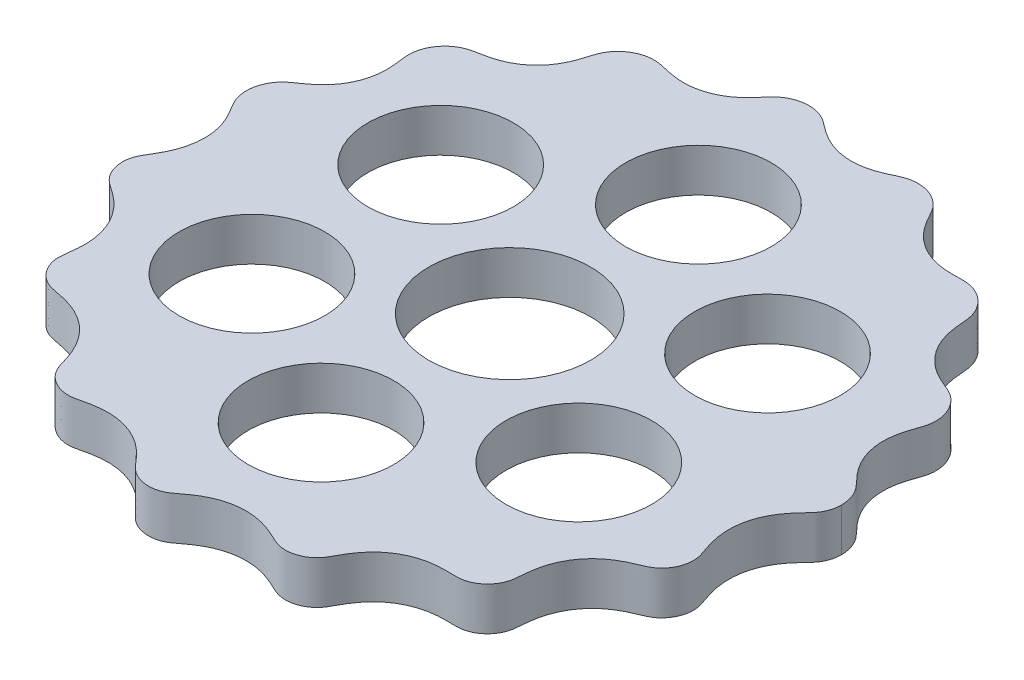
SolidWorks part; units mm, degrees
ref_plane "Front Plane" through (0, 0, 0) normal (0, 0, 1) x (1, 0, 0)
ref_plane "Top Plane" through (0, 0, 0) normal (0, 1, 0) x (1, 0, 0)
ref_plane "Right Plane" through (0, 0, 0) normal (1, 0, 0) x (0, 0, -1)
sketch "Sketch1" plane through (0, 0, 0) normal (0, 1, 0) x (1, 0, 0)
  circle A0 centre (0, 0) radius 35
  circle A1 centre (0, 35) radius 5.5
  circle A2 centre (13.3939, 32.3358) radius 5.5
  circle A3 centre (24.7487, 24.7487) radius 5.5
  circle A4 centre (32.3358, 13.3939) radius 5.5
  circle A5 centre (35, 0) radius 5.5
  circle A6 centre (32.3358, -13.3939) radius 5.5
  circle A7 centre (24.7487, -24.7487) radius 5.5
  circle A8 centre (13.3939, -32.3358) radius 5.5
  circle A9 centre (0, -35) radius 5.5
  circle A10 centre (-13.3939, -32.3358) radius 5.5
  circle A11 centre (-24.7487, -24.7487) radius 5.5
  circle A12 centre (-32.3358, -13.3939) radius 5.5
  circle A13 centre (-35, 0) radius 5.5
  circle A14 centre (-32.3358, 13.3939) radius 5.5
  circle A15 centre (-24.7487, 24.7487) radius 5.5
  circle A16 centre (-13.3939, 32.3358) radius 5.5
  point P37 (0, 0)
  dimension "D1" = 70
  dimension "D2" = 11
  dimension "D3" = 16
sketch "Sketch2" plane through (0, 0, 0) normal (0, 1, 0) x (1, 0, 0)
  line L0 (0, 0) -> (-1.25, 0)
  circle A0 centre (-1.25, 0) radius 7.5
  circle A2 centre (-1.25, 0) radius 17.5
  circle A3 centre (-1.25, 17.5) radius 6.75
  circle A4 centre (13.9054, 8.75) radius 6.75
  circle A5 centre (13.9054, -8.75) radius 6.75
  circle A6 centre (-1.25, -17.5) radius 6.75
  circle A7 centre (-16.4054, -8.75) radius 6.75
  circle A8 centre (-16.4054, 8.75) radius 6.75
  circle A9 centre (35, 0) radius 5.5 construction
  spline S0 degree 4 poles (-31.1366, 6.9847) (-31.203, 6.8351) (-31.3134, 6.5262) (-31.4099, 6.0483) (-31.4002, 5.404) (-31.2697, 4.8647) (-31.0757, 4.4461) (-30.8859, 4.1207) (-30.7324, 3.8696) (-30.5414, 3.5556) (-30.3222, 3.1725) (-30.1219, 2.7738) (-29.947, 2.3583) (-29.8196, 1.9985) (-29.7291, 1.6992) (-29.6529, 1.3958) (-29.5916, 1.0892) (-29.551, 0.8187) (-29.5259, 0.5847) (-29.5113, 0.3932) (-29.5036, 0.2322) (-29.4998, 0.0635) (-29.4996, -0.048) (-29.5028, -0.2) (-29.5088, -0.3457) (-29.52, -0.516) (-29.5395, -0.7199) (-29.5727, -0.9729) (-29.6257, -1.2689) (-29.6959, -1.5759) (-29.7851, -1.8912) (-29.9157, -2.2793) (-30.102, -2.7349) (-30.335, -3.2008) (-30.6126, -3.6776) (-30.9341, -4.194) (-31.2372, -4.7273) (-31.4061, -5.3785) (-31.4057, -6.1172) (-31.2483, -6.8003) (-30.9464, -7.4095) (-30.5187, -7.9124) (-30.0245, -8.2774) (-29.5502, -8.595) (-29.0554, -8.9568) (-28.5566, -9.3788) (-28.0713, -9.8763) (-27.6188, -10.4563) (-27.2335, -11.0884) (-26.9232, -11.7651) (-26.6937, -12.4782) (-26.5492, -13.2173) (-26.4929, -13.9285) (-26.5065, -14.6008) (-26.5673, -15.2309) (-26.6512, -15.8162) (-26.7167, -16.4473) (-26.6264, -17.121) (-26.3588, -17.7823) (-25.9182, -18.3869) (-25.3813, -18.8362) (-24.7951, -19.1235) (-24.2042, -19.2597) (-23.6514, -19.3544) (-23.1491, -19.4609) (-22.7015, -19.5807) (-22.2213, -19.7396) (-21.7138, -19.9467) (-21.1456, -20.242) (-20.5337, -20.6545) (-19.9693, -21.14) (-19.4622, -21.6938) (-19.0208, -22.3087) (-18.6716, -22.937) (-18.4029, -23.561) (-18.1966, -24.1685) (-18.0312, -24.7466) (-17.8368, -25.3596) (-17.4818, -25.9474) (-16.963, -26.4532) (-16.3026, -26.8344) (-15.6052, -27.0309) (-14.9186, -27.0444) (-14.2906, -26.9063) (-13.7073, -26.7605) (-13.0779, -26.6354) (-12.4032, -26.5561) (-11.6845, -26.5443) (-10.9313, -26.6191) (-10.1981, -26.7814) (-9.4956, -27.0274) (-8.9144, -27.311) (-8.4468, -27.5971) (-8.0759, -27.8635) (-7.7913, -28.0922) (-7.4816, -28.3679) (-7.1541, -28.6957) (-6.8107, -29.0774) (-6.4523, -29.5087) (-6.0389, -29.9524) (-5.497, -30.3164) (-4.8394, -30.5567) (-4.0956, -30.636) (-3.389, -30.5371) (-2.7605, -30.2784) (-2.2467, -29.9061) (-1.7817, -29.5409) (-1.2664, -29.1732) (-0.691, -28.8252) (-0.0469, -28.5184) (0.6654, -28.274) (1.3977, -28.1162) (2.139, -28.0466) (2.879, -28.0642) (3.6075, -28.1661) (4.2811, -28.3376) (4.8959, -28.5586) (5.4566, -28.8062) (5.9687, -29.0581) (6.5321, -29.3036) (7.1813, -29.4226) (7.8826, -29.3781) (8.5943, -29.1523) (9.1983, -28.7803) (9.6679, -28.2978) (9.9878, -27.7564) (10.2605, -27.2379) (10.5768, -26.6962) (10.9537, -26.1469) (11.4088, -25.606) (11.9502, -25.0925) (12.5482, -24.6454) (13.1945, -24.2723) (13.8806, -23.9779) (14.596, -23.7658) (15.292, -23.6421) (15.9562, -23.5904) (16.5834, -23.5873) (17.1688, -23.6104) (17.7977, -23.6041) (18.4504, -23.4386) (19.0745, -23.1016) (19.6258, -22.5981) (20.0151, -22.013) (20.2366, -21.3913) (20.3057, -20.7807) (20.3436, -20.2113) (20.4095, -19.6018) (20.5256, -18.9589) (20.7138, -18.2898) (20.9898, -17.608) (21.3446, -16.9582) (21.7755, -16.3511) (22.2783, -15.7958) (22.8461, -15.3011) (23.4339, -14.8967) (24.0229, -14.5724) (24.599, -14.31) (25.1478, -14.0899) (25.7271, -13.8311) (26.2654, -13.4161) (26.7043, -12.8537) (27.0076, -12.1698) (27.1282, -11.4802) (27.084, -10.8288) (26.9064, -10.2491) (26.7122, -9.7229) (26.5247, -9.1481) (26.3661, -8.5215) (26.2605, -7.84) (26.2278, -7.1092) (26.2792, -6.3728) (26.4175, -5.6414) (26.6435, -4.9254) (26.9163, -4.3218) (27.1985, -3.8299) (27.4942, -3.3917) (27.7933, -3.0033) (28.1536, -2.592) (28.5722, -2.1595) (28.9092, -1.79) (29.1246, -1.4556) (29.2527, -1.1931) (29.3238, -1.0179) (29.3829, -0.8388) (29.4302, -0.6555) (29.4612, -0.4933) (29.4803, -0.3554) (29.4914, -0.2338) (29.4973, -0.1324) (29.5007, -0.0226) (29.5, 0.059) (29.4956, 0.1702) (29.4865, 0.2945) (29.4732, 0.4119) (29.4519, 0.545) (29.4193, 0.6991) (29.3684, 0.8884) (29.2999, 1.0847) (29.211, 1.2861) (29.099, 1.4891) (28.9873, 1.6605) (28.8641, 1.8237) (28.732, 1.9798) (28.56, 2.1688) (28.311, 2.4302) (27.9922, 2.7711) (27.6241, 3.2099) (27.2613, 3.7219) (26.8678, 4.4005) (26.5022, 5.2703) (26.3208, 6.0377) (26.2588, 6.6626) (26.2483, 6.9757) knots 0 0 0 0 0 0.005587 0.011173 0.016507 0.02184 0.02435 0.026861 0.029371 0.031882 0.036903 0.041924 0.044592 0.04726 0.049928 0.052596 0.055264 0.057932 0.059266 0.0606 0.061934 0.063268 0.064442 0.065615 0.066789 0.067963 0.070311 0.072658 0.075454 0.07825 0.081046 0.083842 0.089434 0.095025 0.098832 0.102639 0.110253 0.115841 0.12143 0.127693 0.133956 0.138834 0.143712 0.148591 0.153469 0.159735 0.166 0.172266 0.178532 0.184946 0.191361 0.197775 0.20419 0.209244 0.214299 0.219354 0.224409 0.23082 0.23723 0.243461 0.249691 0.254486 0.25928 0.264075 0.26887 0.271986 0.275101 0.281333 0.287565 0.293796 0.300242 0.306689 0.313135 0.319581 0.324722 0.329863 0.335004 0.340145 0.346588 0.353031 0.359474 0.365917 0.371058 0.376199 0.38134 0.386481 0.392928 0.399374 0.40582 0.412266 0.418498 0.424729 0.427845 0.430961 0.434077 0.437193 0.441987 0.446782 0.451577 0.456371 0.462602 0.468832 0.475243 0.481654 0.486709 0.491763 0.496818 0.501873 0.508287 0.514702 0.521116 0.527531 0.533796 0.540062 0.546328 0.552593 0.557472 0.56235 0.567228 0.572107 0.57837 0.584633 0.590985 0.597337 0.602346 0.607354 0.612363 0.617371 0.623727 0.630083 0.636439 0.642795 0.649151 0.655506 0.661862 0.668218 0.673227 0.678235 0.683244 0.688252 0.694604 0.700957 0.70722 0.713483 0.718361 0.723239 0.728118 0.732996 0.739262 0.745527 0.751793 0.758059 0.764473 0.770888 0.777302 0.783717 0.788771 0.793826 0.798881 0.803936 0.810347 0.816757 0.822988 0.829218 0.834013 0.838807 0.843602 0.848397 0.854628 0.86086 0.867092 0.873323 0.879769 0.886216 0.892662 0.895885 0.899108 0.904249 0.90939 0.914531 0.919672 0.921283 0.922894 0.924505 0.926115 0.927726 0.929337 0.930142 0.930947 0.931753 0.932558 0.933896 0.934564 0.935233 0.93657 0.937908 0.939245 0.940582 0.943257 0.945002 0.946746 0.948491 0.950235 0.95198 0.953724 0.957213 0.962562 0.967911 0.973259 0.978608 0.989304 1 1 1 1 1 construction
  spline S1 degree 4 poles (-29.5, 0) (-29.5, -0.0299) (-29.5005, -0.0898) (-29.5028, -0.2) (-29.5088, -0.3457) (-29.52, -0.516) (-29.5395, -0.7199) (-29.5727, -0.9729) (-29.6257, -1.2689) (-29.6959, -1.5759) (-29.7851, -1.8912) (-29.9157, -2.2793) (-30.102, -2.7349) (-30.335, -3.2008) (-30.6126, -3.6776) (-30.9341, -4.194) (-31.2372, -4.7273) (-31.4061, -5.3785) (-31.4057, -6.1172) (-31.2483, -6.8003) (-30.9464, -7.4095) (-30.5187, -7.9124) (-30.0245, -8.2774) (-29.5502, -8.595) (-29.0554, -8.9568) (-28.5566, -9.3788) (-28.0713, -9.8763) (-27.6188, -10.4563) (-27.2335, -11.0884) (-26.9232, -11.7651) (-26.6937, -12.4782) (-26.5492, -13.2173) (-26.4929, -13.9285) (-26.5065, -14.6008) (-26.5673, -15.2309) (-26.6512, -15.8162) (-26.7167, -16.4473) (-26.6264, -17.121) (-26.3588, -17.7823) (-25.9182, -18.3869) (-25.3813, -18.8362) (-24.7951, -19.1235) (-24.2042, -19.2597) (-23.6514, -19.3544) (-23.1491, -19.4609) (-22.7015, -19.5807) (-22.2213, -19.7396) (-21.7138, -19.9467) (-21.1456, -20.242) (-20.5337, -20.6545) (-19.9693, -21.14) (-19.4622, -21.6938) (-19.0208, -22.3087) (-18.6716, -22.937) (-18.4029, -23.561) (-18.1966, -24.1685) (-18.0312, -24.7466) (-17.8368, -25.3596) (-17.4818, -25.9474) (-16.963, -26.4532) (-16.3026, -26.8344) (-15.6052, -27.0309) (-14.9186, -27.0444) (-14.2906, -26.9063) (-13.7073, -26.7605) (-13.0779, -26.6354) (-12.4032, -26.5561) (-11.6845, -26.5443) (-10.9313, -26.6191) (-10.1981, -26.7814) (-9.4956, -27.0274) (-8.9144, -27.311) (-8.4468, -27.5971) (-8.0759, -27.8635) (-7.7913, -28.0922) (-7.4816, -28.3679) (-7.1541, -28.6957) (-6.8107, -29.0774) (-6.4523, -29.5087) (-6.0389, -29.9524) (-5.497, -30.3164) (-4.8394, -30.5567) (-4.0956, -30.636) (-3.389, -30.5371) (-2.7605, -30.2784) (-2.2467, -29.9061) (-1.7817, -29.5409) (-1.2664, -29.1732) (-0.691, -28.8252) (-0.0469, -28.5184) (0.6654, -28.274) (1.3977, -28.1162) (2.139, -28.0466) (2.879, -28.0642) (3.6075, -28.1661) (4.2811, -28.3376) (4.8959, -28.5586) (5.4566, -28.8062) (5.9687, -29.0581) (6.5321, -29.3036) (7.1813, -29.4226) (7.8826, -29.3781) (8.5943, -29.1523) (9.1983, -28.7803) (9.6679, -28.2978) (9.9878, -27.7564) (10.2605, -27.2379) (10.5768, -26.6962) (10.9537, -26.1469) (11.4088, -25.606) (11.9502, -25.0925) (12.5482, -24.6454) (13.1945, -24.2723) (13.8806, -23.9779) (14.596, -23.7658) (15.292, -23.6421) (15.9562, -23.5904) (16.5834, -23.5873) (17.1688, -23.6104) (17.7977, -23.6041) (18.4504, -23.4386) (19.0745, -23.1016) (19.6258, -22.5981) (20.0151, -22.013) (20.2366, -21.3913) (20.3057, -20.7807) (20.3436, -20.2113) (20.4095, -19.6018) (20.5256, -18.9589) (20.7138, -18.2898) (20.9898, -17.608) (21.3446, -16.9582) (21.7755, -16.3511) (22.2783, -15.7958) (22.8461, -15.3011) (23.4339, -14.8967) (24.0229, -14.5724) (24.599, -14.31) (25.1478, -14.0899) (25.7271, -13.8311) (26.2654, -13.4161) (26.7043, -12.8537) (27.0076, -12.1698) (27.1282, -11.4802) (27.084, -10.8288) (26.9064, -10.2491) (26.7122, -9.7229) (26.5247, -9.1481) (26.3661, -8.5215) (26.2605, -7.84) (26.2278, -7.1092) (26.2792, -6.3728) (26.4175, -5.6414) (26.6435, -4.9254) (26.9163, -4.3218) (27.1985, -3.8299) (27.4942, -3.3917) (27.7933, -3.0033) (28.1536, -2.592) (28.5722, -2.1595) (28.9092, -1.79) (29.1246, -1.4556) (29.2527, -1.1931) (29.3238, -1.0179) (29.3829, -0.8388) (29.4302, -0.6555) (29.4612, -0.4933) (29.4803, -0.3554) (29.4914, -0.2338) (29.4973, -0.1324) (29.4995, -0.0617) (29.5, -0.0205) (29.5, 0) knots 0.063268 0.063268 0.063268 0.063268 0.063268 0.064442 0.065615 0.066789 0.067963 0.070311 0.072658 0.075454 0.07825 0.081046 0.083842 0.089434 0.095025 0.098832 0.102639 0.110253 0.115841 0.12143 0.127693 0.133956 0.138834 0.143712 0.148591 0.153469 0.159735 0.166 0.172266 0.178532 0.184946 0.191361 0.197775 0.20419 0.209244 0.214299 0.219354 0.224409 0.23082 0.23723 0.243461 0.249691 0.254486 0.25928 0.264075 0.26887 0.271986 0.275101 0.281333 0.287565 0.293796 0.300242 0.306689 0.313135 0.319581 0.324722 0.329863 0.335004 0.340145 0.346588 0.353031 0.359474 0.365917 0.371058 0.376199 0.38134 0.386481 0.392928 0.399374 0.40582 0.412266 0.418498 0.424729 0.427845 0.430961 0.434077 0.437193 0.441987 0.446782 0.451577 0.456371 0.462602 0.468832 0.475243 0.481654 0.486709 0.491763 0.496818 0.501873 0.508287 0.514702 0.521116 0.527531 0.533796 0.540062 0.546328 0.552593 0.557472 0.56235 0.567228 0.572107 0.57837 0.584633 0.590985 0.597337 0.602346 0.607354 0.612363 0.617371 0.623727 0.630083 0.636439 0.642795 0.649151 0.655506 0.661862 0.668218 0.673227 0.678235 0.683244 0.688252 0.694604 0.700957 0.70722 0.713483 0.718361 0.723239 0.728118 0.732996 0.739262 0.745527 0.751793 0.758059 0.764473 0.770888 0.777302 0.783717 0.788771 0.793826 0.798881 0.803936 0.810347 0.816757 0.822988 0.829218 0.834013 0.838807 0.843602 0.848397 0.854628 0.86086 0.867092 0.873323 0.879769 0.886216 0.892662 0.895885 0.899108 0.904249 0.90939 0.914531 0.919672 0.921283 0.922894 0.924505 0.926115 0.927726 0.929337 0.930142 0.930947 0.931753 0.932558 0.932558 0.932558 0.932558 0.932558
  spline S2 degree 4 poles (-29.5, 0) (-29.5, 0.0364) (-29.5006, 0.0913) (-29.5027, 0.1851) (-29.5101, 0.3614) (-29.5228, 0.5258) (-29.544, 0.7224) (-29.5765, 0.9381) (-29.6087, 1.1148) (-29.6557, 1.3343) (-29.7228, 1.5951) (-29.8163, 1.8952) (-29.9429, 2.2314) (-30.088, 2.5599) (-30.2495, 2.8808) (-30.4371, 3.2152) (-30.6483, 3.5644) (-30.8763, 3.9316) (-31.0909, 4.336) (-31.2721, 4.8276) (-31.3776, 5.409) (-31.3713, 6.0755) (-31.2074, 6.8007) (-30.8574, 7.5539) (-30.258, 8.2678) (-29.4718, 8.7488) (-28.737, 9.2911) (-28.124, 9.8641) (-27.6404, 10.4475) (-27.1296, 11.2544) (-26.7683, 12.1461) (-26.5719, 13.0909) (-26.539, 14.0023) (-26.5831, 14.6672) (-26.6624, 15.2755) (-26.7381, 15.8323) (-26.7424, 16.4485) (-26.61, 17.1063) (-26.3244, 17.7644) (-25.8718, 18.3837) (-25.2431, 18.9372) (-24.4159, 19.3511) (-23.5097, 19.4755) (-22.6243, 19.664) (-21.8356, 19.931) (-21.1592, 20.2576) (-20.5227, 20.6717) (-19.9433, 21.1709) (-19.431, 21.7482) (-18.998, 22.3942) (-18.6738, 23.0428) (-18.4387, 23.6718) (-18.2601, 24.2638) (-18.1039, 24.8079) (-17.8606, 25.3793) (-17.4739, 25.9338) (-16.9395, 26.4293) (-16.2625, 26.8203) (-15.5662, 27.0352) (-14.8926, 27.0929) (-14.2761, 27.0178) (-13.7268, 26.8812) (-13.1249, 26.7397) (-12.4624, 26.6291) (-11.5448, 26.5733) (-10.5808, 26.6799) (-9.658, 26.9567) (-8.8078, 27.3886) (-8.1867, 27.8113) (-7.5612, 28.3607) (-6.9551, 29.0333) (-6.3943, 29.7558) (-5.6223, 30.2653) (-4.8286, 30.533) (-4.066, 30.6153) (-3.3532, 30.5336) (-2.7174, 30.3193) (-2.1859, 30.0075) (-1.7416, 29.6635) (-1.2544, 29.2908) (-0.7006, 28.9201) (0.1051, 28.4929) (1.0216, 28.1906) (1.9744, 28.0577) (2.9287, 28.0966) (3.6757, 28.2236) (4.4784, 28.4681) (5.3155, 28.8331) (6.125, 29.2738) (7.0433, 29.4355) (7.8824, 29.3616) (8.6158, 29.129) (9.3527, 28.7001) (10.0228, 28.0203) (10.4257, 27.1676) (10.9001, 26.3629) (11.5365, 25.5319) (12.3845, 24.745) (13.3938, 24.1623) (14.4992, 23.8213) (15.5372, 23.6857) (16.4713, 23.6772) (17.4111, 23.7546) (18.335, 23.5142) (19.0748, 23.0905) (19.643, 22.5716) (20.1265, 21.8819) (20.4456, 21.0058) (20.4687, 20.0844) (20.5711, 19.1769) (20.7608, 18.3596) (21.0243, 17.6491) (21.4677, 16.8032) (22.0593, 16.0445) (22.7792, 15.402) (23.5521, 14.9179) (24.15, 14.6236) (24.7164, 14.388) (25.2365, 14.1752) (25.7722, 13.8709) (26.2757, 13.4273) (26.7029, 12.8509) (27.0129, 12.1493) (27.1779, 11.3281) (27.1227, 10.4048) (26.7774, 9.5578) (26.4979, 8.6967) (26.3348, 7.8802) (26.2794, 7.1311) (26.3199, 6.3728) (26.4624, 5.6214) (26.7063, 4.8891) (27.0491, 4.1911) (27.4488, 3.5862) (27.8759, 3.0679) (28.2996, 2.6175) (28.6922, 2.2097) (28.9783, 1.8306) (29.1605, 1.4959) (29.2732, 1.2321) (29.3381, 1.0493) (29.3924, 0.8633) (29.4358, 0.6744) (29.4643, 0.5063) (29.4819, 0.3649) (29.4921, 0.2412) (29.4975, 0.1366) (29.4995, 0.0632) (29.5, 0.0209) (29.5, 0) knots 0.065559 0.065559 0.065559 0.065559 0.065559 0.06699 0.067705 0.06842 0.071281 0.072807 0.074333 0.075859 0.077385 0.080438 0.08349 0.086542 0.089594 0.092646 0.095698 0.099582 0.103466 0.10735 0.111234 0.117337 0.123439 0.129867 0.136295 0.145418 0.154541 0.160971 0.167402 0.173832 0.180263 0.193345 0.199887 0.206428 0.211202 0.215977 0.220751 0.225525 0.232063 0.238601 0.244977 0.251353 0.260403 0.269454 0.275832 0.28221 0.288588 0.294966 0.30156 0.308153 0.314746 0.32134 0.326151 0.330962 0.335773 0.340584 0.347174 0.353763 0.360353 0.366942 0.371753 0.376564 0.381375 0.386187 0.39278 0.399373 0.41256 0.418938 0.425316 0.431694 0.438073 0.447123 0.456173 0.462549 0.468925 0.475463 0.482001 0.486775 0.49155 0.496324 0.501098 0.507639 0.514181 0.527264 0.533694 0.540124 0.546555 0.552985 0.562108 0.571231 0.577659 0.584087 0.590604 0.59712 0.606506 0.615892 0.62241 0.628929 0.641967 0.655004 0.661523 0.668042 0.677428 0.686813 0.69333 0.699846 0.706274 0.712702 0.721825 0.730948 0.737379 0.743809 0.750239 0.75667 0.769753 0.776294 0.782835 0.78761 0.792384 0.797158 0.801932 0.80847 0.815008 0.821384 0.82776 0.836811 0.845861 0.852239 0.858617 0.864995 0.871373 0.877967 0.88456 0.891154 0.897747 0.902558 0.907369 0.91218 0.916991 0.918639 0.920286 0.921933 0.923581 0.925228 0.926876 0.927699 0.928523 0.929347 0.93017 0.93017 0.93017 0.93017 0.93017
  point P12 (29.5, 0)
  point P23 (-1.25, 0)
  dimension "D3" = 15
  dimension "D4" = 35
  dimension "D5" = 13.5
  dimension "D1" = 1.25
  dimension "D6" = 6
extrude "Boss-Extrude1" add sketch "Sketch2" along normal blind 4 contours S2 S1 A8 A2 A3 A4 A5 A6 A7 | A8 A2 A7 A6 A5 A4 A3 A0
sketch "Sketch3" plane through (0, 4, 0) normal (0, 1, 0) x (1, 0, 0)
  circle A0 centre (0, 0) radius 17.5
  circle A1 centre (0, 17.5) radius 5.5
  circle A2 centre (15.1554, 8.75) radius 5.5
  circle A3 centre (15.1554, -8.75) radius 5.5
  circle A4 centre (0, -17.5) radius 5.5
  circle A5 centre (-15.1554, -8.75) radius 5.5
  circle A6 centre (-15.1554, 8.75) radius 5.5
  point P16 (0, 0)
  dimension "D2" = 11
  dimension "D1" = 35
  dimension "D3" = 6
equation "\"R_SUN\"= 35"
equation "\"D1@Sketch1\"=2*\"R_SUN\""
equation "\"R_ROLL\"= 5.5"
equation "\"D2@Sketch1\"=2*\"R_ROLL\""
equation "\"GRATIO\"= 15"
equation "\"RHO\"= 1.25"
equation "\"D1@Sketch2\"=\"RHO\""
equation "\"D_IN\"= 15"
equation "\"D3@Sketch2\"=\"D_IN\""
equation "\"D_OUT_HOLES\"= 35"
equation "\"D4@Sketch2\"=\"D_OUT_HOLES\""
equation "\"R_OUT\"= 11"
equation "\"D5@Sketch2\"=\"R_OUT\"+2*\"RHO\""
equation "\"NUM_OUT\"=6"
equation "\"D6@Sketch2\"=\"NUM_OUT\""
equation "\"Thick\"= 4"
equation "\"D1@Boss-Extrude1\"=\"Thick\""
equation "\"D_BOLTS\"=35"
equation "\"D1@Sketch3\"=\"D_BOLTS\""
equation "\"BOLT_D\"=11"
equation "\"D2@Sketch3\"=\"BOLT_D\""
equation "\"D3@Sketch3\"=\"NUM_OUT\""
